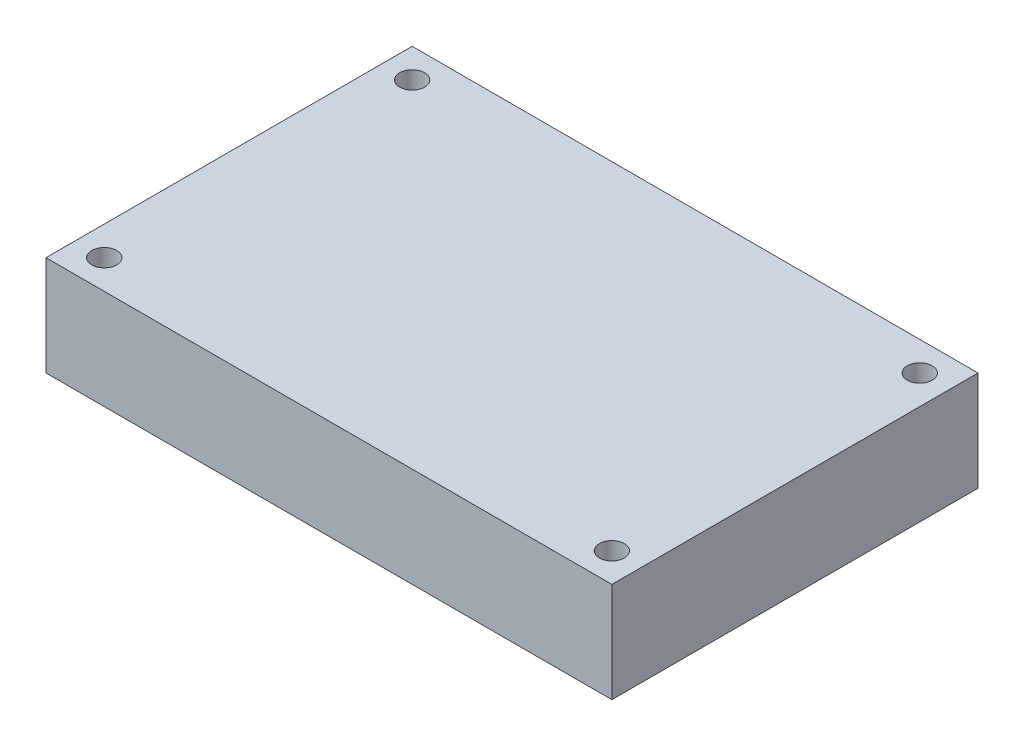
SolidWorks part; units mm, degrees
ref_plane "前视基准面" through (0, 0, 0) normal (0, 0, 1) x (1, 0, 0)
ref_plane "上视基准面" through (0, 0, 0) normal (0, 1, 0) x (1, 0, 0)
ref_plane "右视基准面" through (0, 0, 0) normal (1, 0, 0) x (0, 0, -1)
sketch "草图1" plane through (0, 0, 0) normal (0, 1, 0) x (1, 0, 0)
  line L1 (-30.5, 18.5) -> (30.5, 18.5) construction
  line L2 (-30.5, 18.5) -> (-30.5, -18.5) construction
  line L3 (-30.5, -18.5) -> (30.5, -18.5) construction
  line L4 (30.5, 18.5) -> (30.5, -18.5) construction
  line L5 (-30.5, 18.5) -> (30.5, -18.5) construction
  line L6 (-30.5, -18.5) -> (30.5, 18.5) construction
  line L7 (-34, 22) -> (34, 22)
  line L8 (-34, 22) -> (-34, -22)
  line L9 (-34, -22) -> (34, -22)
  line L10 (34, 22) -> (34, -22)
  line L11 (-34, 22) -> (34, -22) construction
  line L12 (-34, -22) -> (34, 22) construction
  circle A0 centre (-30.5, 18.5) radius 1.5
  circle A1 centre (-30.5, -18.5) radius 1.5
  circle A2 centre (30.5, -18.5) radius 1.5
  circle A3 centre (30.5, 18.5) radius 1.5
  point P0 (0, 0)
  point P6 (0, 0)
  dimension "D5" = 3
  dimension "D6" = 3
  dimension "D7" = 3
  dimension "D8" = 3
  dimension "D1" = 61
  dimension "D2" = 37
  dimension "D3" = 68
  dimension "D4" = 44
extrude "凸台-拉伸1" add sketch "草图1" along normal blind 12
